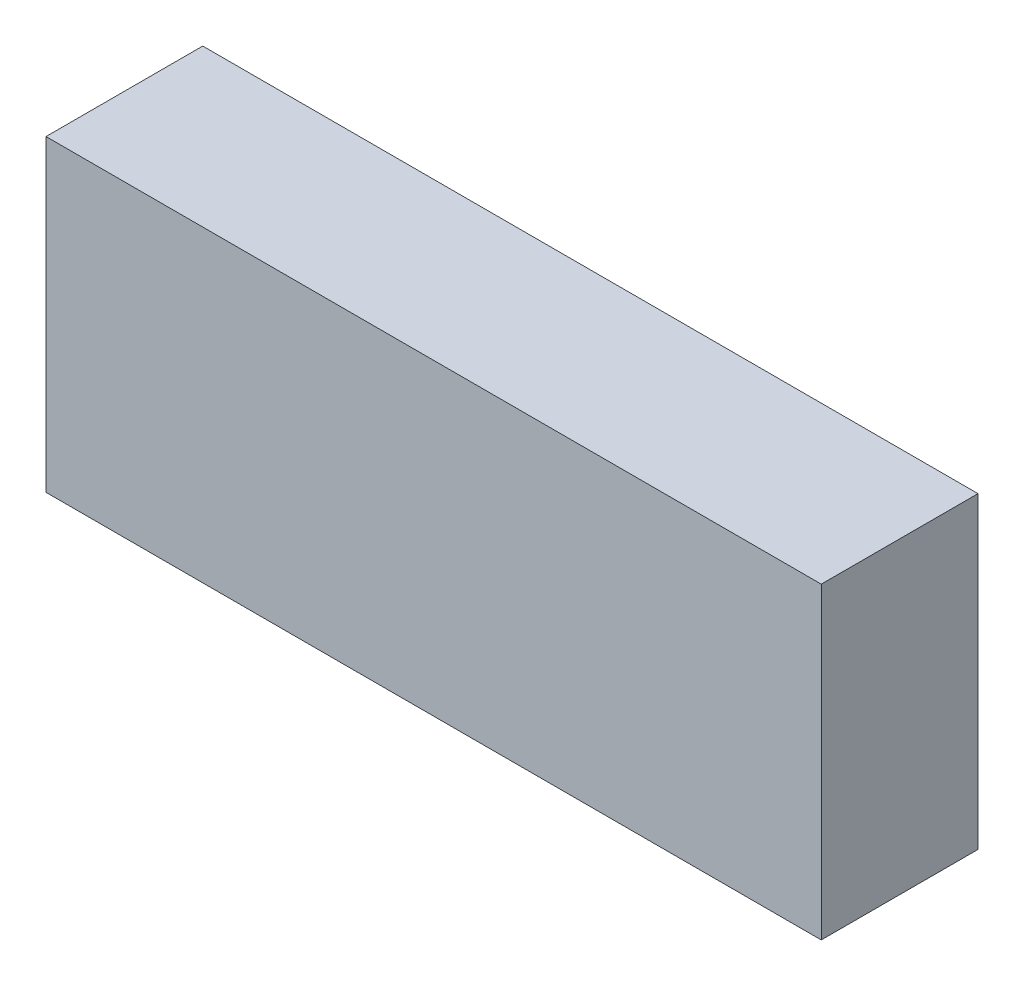
SolidWorks part; units mm, degrees
ref_plane "Ebene vorne" through (0, 0, 0) normal (0, 0, 1) x (1, 0, 0)
ref_plane "Ebene oben" through (0, 0, 0) normal (0, 1, 0) x (1, 0, 0)
ref_plane "Ebene rechts" through (0, 0, 0) normal (1, 0, 0) x (0, 0, -1)
sketch "Skizze1" plane through (0, 0, 0) normal (0, 0, 1) x (1, 0, 0)
  line L0 (-2.473, 0.983) -> (2.473, 0.983)
  line L1 (2.473, 0.983) -> (2.473, -0.983)
  line L2 (2.473, -0.983) -> (-2.473, -0.983)
  line L3 (-2.473, -0.983) -> (-2.473, 0.983)
extrude "Component_Outline" add sketch "Skizze1" along normal blind 1 separate body
sketch3d "3D-Skizze1"
  line L0 (0, 0, 0) -> (1, 0, 0)
  line L1 (0, 0, 0) -> (0, 1, 0)
  line L2 (0, 0, 0) -> (0, 0, 1)
  point P0 (0, 0, 0)
